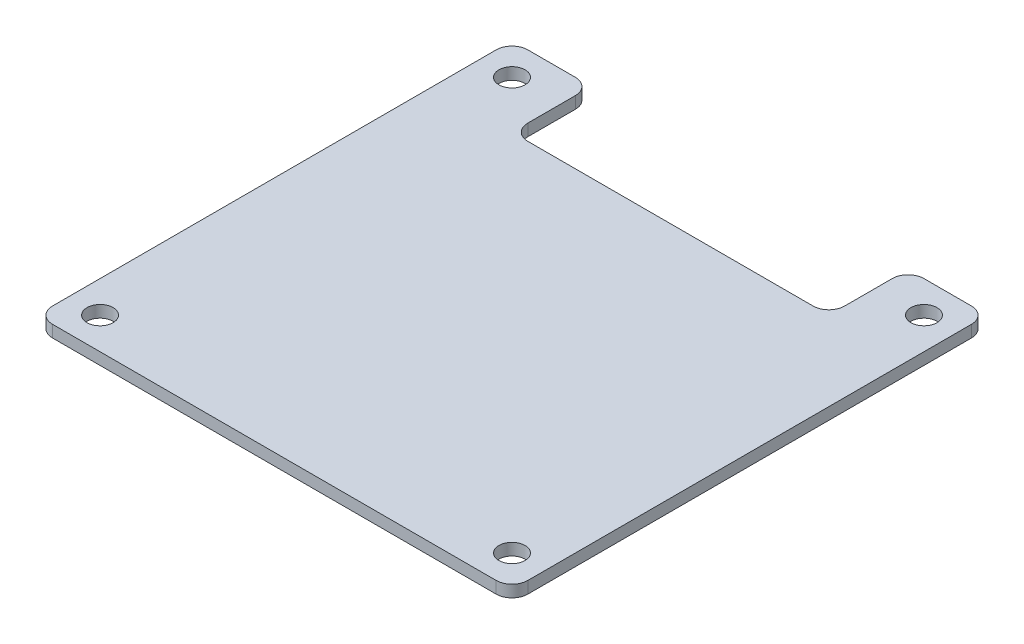
SolidWorks part; units mm, degrees
ref_plane "Спереди" through (0, 0, 0) normal (0, 0, 1) x (1, 0, 0)
ref_plane "Сверху" through (0, 0, 0) normal (0, 1, 0) x (1, 0, 0)
ref_plane "Справа" through (0, 0, 0) normal (1, 0, 0) x (0, 0, -1)
sketch "Эскиз1" plane through (0, 0, 0) normal (0, 1, 0) x (1, 0, 0)
  line L0 (0, 46.3064) -> (0, -45.6827) construction
  line L1 (-144.6921, 0) -> (-66.9305, 0) construction
  line L2 (20, 30) -> (30, 30)
  line L3 (-30, 30) -> (-20, 30)
  line L4 (-30, 30) -> (-30, -30)
  line L5 (-30, -30) -> (30, -30)
  line L6 (30, 30) -> (30, -30)
  line L7 (-26, 26) -> (26, 26) construction
  line L8 (-26, 26) -> (-26, -26) construction
  line L9 (-26, -26) -> (26, -26) construction
  line L10 (26, 26) -> (26, -26) construction
  line L12 (-20, 30) -> (-20, 22)
  line L13 (-18, 20) -> (18, 20)
  line L14 (20, 30) -> (20, 22)
  circle A0 centre (-26, 26) radius 1.65
  circle A1 centre (26, 26) radius 1.65
  circle A2 centre (-26, -26) radius 1.65
  circle A3 centre (26, -26) radius 1.65
  arc A4 (-18, 20) -> (-20, 22) centre (-18, 22) cw
  arc A5 (20, 22) -> (18, 20) centre (18, 22) cw
  point P24 (-20, 20)
  point P27 (20, 20)
  dimension "D3" = 3.3
  dimension "D6" = 2
  dimension "D7" = 2
  dimension "D1" = 60
  dimension "D2" = 52
  dimension "D4" = 10
  dimension "D5" = 40
extrude "Бобышка-Вытянуть1" add sketch "Эскиз1" along normal blind 1.5
fillet "Скругление1" radius 2 1 edges at (-30, 0.75, 30)
fillet "Скругление2" radius 2 5 edges at (30, 0.75, 30) (30, 0.75, -30) (20, 0.75, -30) (-20, 0.75, -30) (-30, 0.75, -30)
